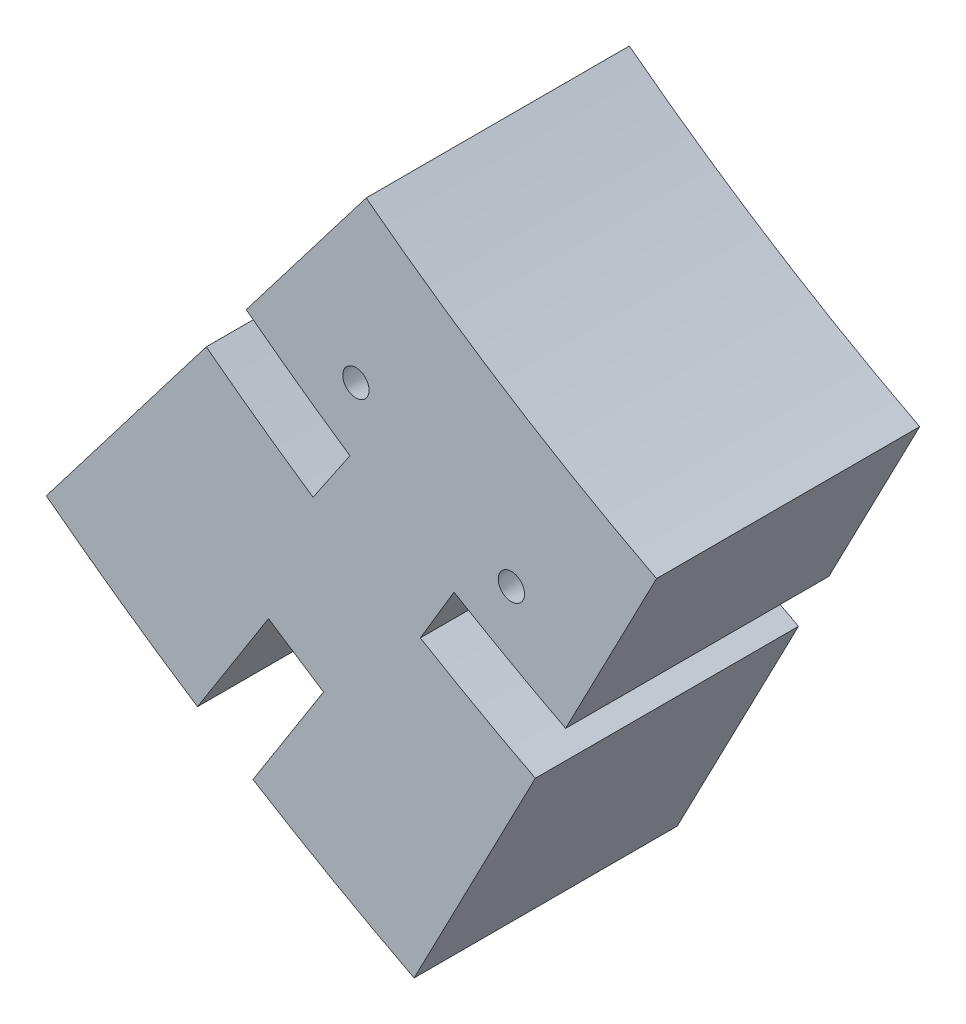
SolidWorks part; units mm, degrees
ref_plane "前视基准面" through (0, 0, 0) normal (0, 0, 1) x (1, 0, 0)
ref_plane "上视基准面" through (0, 0, 0) normal (0, 1, 0) x (1, 0, 0)
ref_plane "右视基准面" through (0, 0, 0) normal (1, 0, 0) x (0, 0, -1)
sketch "草图1" plane through (0, 0, 0) normal (0, 0, 1) x (1, 0, 0)
  line L0 (-455.8378, -595.5769) -> (-577.3946, -754.3975)
  line L1 (-345.4918, -665.6842) -> (-437.6229, -843.2)
  arc A0 (-577.3946, -754.3975) -> (-437.6229, -843.2) centre (0, 0) ccw
  arc A1 (-455.8378, -595.5769) -> (-345.4918, -665.6842) centre (0, 0) ccw
extrude "凸台-拉伸1" add sketch "草图1" along normal blind 100
sketch "草图2" plane through (0, 0, 100) normal (0, 0, 1) x (1, 0, 0)
  line L0 (0, 0) -> (-482.5902, -759.578) construction
  line L3 (-472.0395, -766.2812) -> (-498.8526, -808.4838)
  line L6 (-492.9679, -752.6024) -> (-519.9504, -795.0796)
  line L9 (-519.9504, -795.0796) -> (-523.1953, -798.3245)
  line L10 (-523.1953, -798.3245) -> (-500.2934, -812.5994)
  line L12 (-498.8526, -808.4838) -> (-500.2934, -812.5994)
  line L13 (-492.9679, -752.6024) -> (-472.0395, -766.2812)
  arc A0 (-577.3946, -754.3975) -> (-437.6229, -843.2) centre (0, 0) ccw construction
  dimension "D1" = 12.5
  dimension "D2" = 12.5
  dimension "D3" = 50
extrude "切除-拉伸1" cut sketch "草图2" against normal through all
sketch "草图3" plane through (0, 0, 100) normal (0, 0, 1) x (1, 0, 0)
  line L0 (0, 0) -> (-482.5037, -759.4418) construction
  line L1 (-472.0395, -766.2812) -> (-492.9679, -752.6024) construction
  line L2 (-491.9485, -662.4215) -> (-427.526, -654.2614) construction
  line L5 (-449.7458, -689.2345) -> (-427.526, -654.2614)
  line L7 (-427.526, -654.2614) -> (-469.7286, -627.4484)
  line L8 (-469.7286, -627.4484) -> (-491.9485, -662.4215)
  line L9 (-491.9485, -662.4215) -> (-449.7458, -689.2345)
  line L10 (-469.7286, -627.4484) -> (-449.7458, -689.2345) construction
  point P7 (-459.7372, -658.3415)
  dimension "D1" = 50
  dimension "D2" = 10
ref_plane "基准面1" through (-29.5994, 18.8022, 0) normal (0.8441, -0.5362, 0) x (0, 0, -1)
sketch "草图4" plane through (-29.5994, 18.8022, 0) normal (0.8441, -0.5362, 0) x (0, 0, -1)
  line L0 (-100, -802.2108) -> (-100, -797.2108)
  line L1 (-100, -797.2108) -> (-50.7596, -788.5284)
  line L2 (-50.7596, -788.5284) -> (0, -788.5284)
  line L3 (0, -788.5284) -> (0, -802.2108)
  line L5 (-100, -802.2108) -> (0, -802.2108)
  dimension "D1" = 5
  dimension "D2" = 50
  dimension "D3" = 100
  dimension "D4" = 80
revolve "切除-旋转1" cut sketch "草图4" angle 360 about L5
ref_plane "基准面2" through (0, 0, 0) normal (-0.8441, 0.5363, 0) x (0, 0, 1)
mirror "镜向1" about plane through (0, 0, 0) normal (-0.8441, 0.5363, 0) of "切除-旋转1"
sketch "草图6" plane through (0, 0, 100) normal (0, 0, 1) x (1, 0, 0)
  line L0 (-501.4216, -655.1346) -> (-516.6075, -674.9758)
  line L1 (-455.8378, -595.5769) -> (-577.3946, -754.3975) construction
  line L2 (-462.0153, -683.4961) -> (-476.0078, -704.1962)
  line L3 (-380.0409, -732.2526) -> (-391.5507, -754.4294)
  line L4 (-437.6229, -843.2) -> (-345.4918, -665.6842) construction
  line L5 (-422.4565, -708.6293) -> (-435.2509, -730.0906)
  arc A0 (-516.6075, -674.9758) -> (-476.0078, -704.1962) centre (0, 0) ccw
  arc A1 (-501.4216, -655.1346) -> (-462.0153, -683.4961) centre (0, 0) ccw
  arc A2 (-422.4565, -708.6293) -> (-380.0409, -732.2526) centre (0, 0) ccw
  arc A3 (-435.2509, -730.0906) -> (-391.5507, -754.4294) centre (0, 0) ccw
  dimension "D1" = 50
extrude "切除-拉伸2" cut sketch "草图6" against normal blind 100
